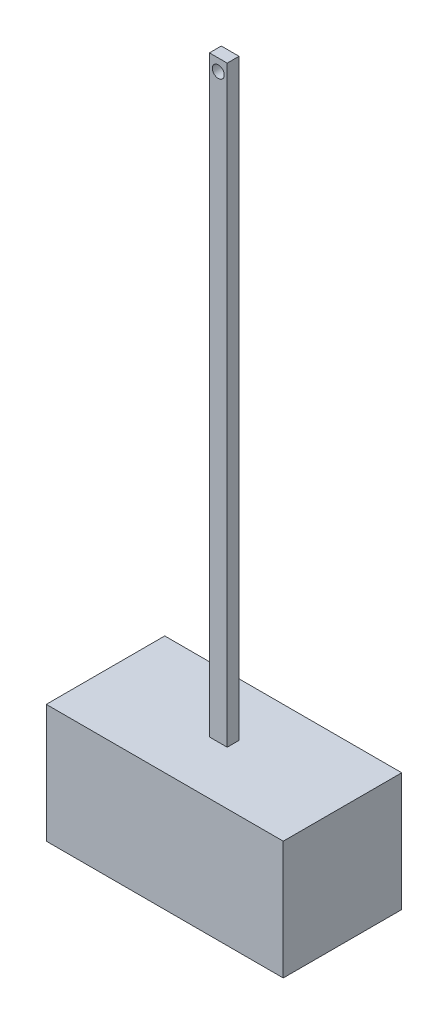
SolidWorks part; units mm, degrees
ref_plane "Front Plane" through (0, 0, 0) normal (0, 0, 1) x (1, 0, 0)
ref_plane "Top Plane" through (0, 0, 0) normal (0, 1, 0) x (1, 0, 0)
ref_plane "Right Plane" through (0, 0, 0) normal (1, 0, 0) x (0, 0, -1)
sketch "Sketch1" plane through (0, 0, 0) normal (0, 0, 1) x (1, 0, 0)
  line L1 (-7.5, 10) -> (7.5, 10)
  line L2 (-7.5, 10) -> (-7.5, -490)
  line L3 (-7.5, -490) -> (7.5, -490)
  line L4 (7.5, 10) -> (7.5, -490)
  circle A0 centre (0, 0) radius 5
  point P9 (-39.1637, 22.961)
  dimension "D1" = 10
  dimension "D2" = 10
  dimension "D3" = 15
  dimension "D4" = 7.5
  dimension "D5" = 500
extrude "Boss-Extrude1" add sketch "Sketch1" along normal blind 10
sketch "Sketch2" plane through (0, -490, 0) normal (0, -1, 0) x (1, 0, 0)
  line L0 (7.5, 10) -> (7.5, 0) construction
  line L1 (-100.2, 55) -> (99.8, 55)
  line L2 (-100.2, 55) -> (-100.2, -45)
  line L3 (-100.2, -45) -> (99.8, -45)
  line L4 (99.8, 55) -> (99.8, -45)
  line L5 (-100.2, 55) -> (99.8, -45) construction
  line L6 (-100.2, -45) -> (99.8, 55) construction
  line L8 (-7.5, 0) -> (7.5, 0) construction
  point P0 (-0.2, 5)
  dimension "D1" = 100
  dimension "D2" = 200
  dimension "D3" = 7.7
  dimension "D4" = 5
extrude "Boss-Extrude2" add sketch "Sketch2" along normal blind 100
